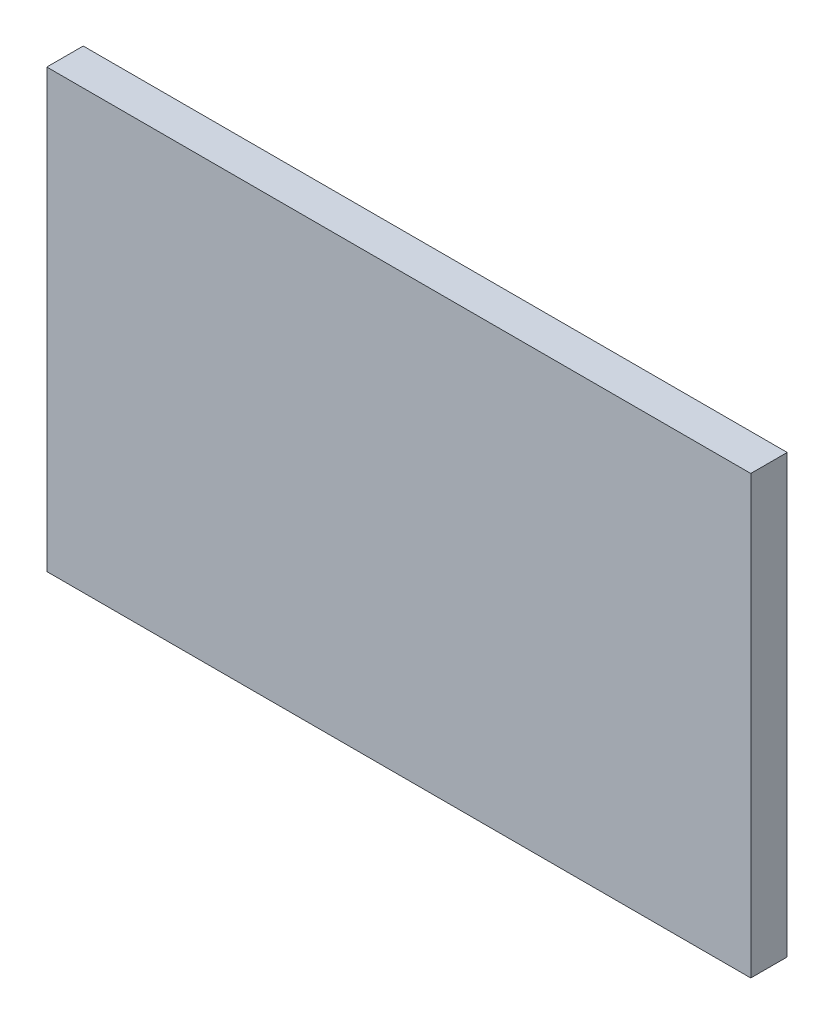
SolidWorks part; units mm, degrees
ref_plane "Front Plane" through (0, 0, 0) normal (0, 0, 1) x (1, 0, 0)
ref_plane "Top Plane" through (0, 0, 0) normal (0, 1, 0) x (1, 0, 0)
ref_plane "Right Plane" through (0, 0, 0) normal (1, 0, 0) x (0, 0, -1)
sketch "Sketch1" plane through (0, 0, 0) normal (0, 1, 0) x (1, 0, 0)
  line L1 (-7, 0.25) -> (7.5, 0.25)
  line L2 (-7, 0.25) -> (-7, -0.5)
  line L3 (-7, -0.5) -> (7.5, -0.5)
  line L4 (7.5, 0.25) -> (7.5, -0.5)
  dimension "D1" = 14.5
  dimension "D2" = 0.75
  dimension "D3" = 0.5
  dimension "D4" = 7.5
extrude "Boss-Extrude1" add sketch "Sketch1" along normal blind 9
